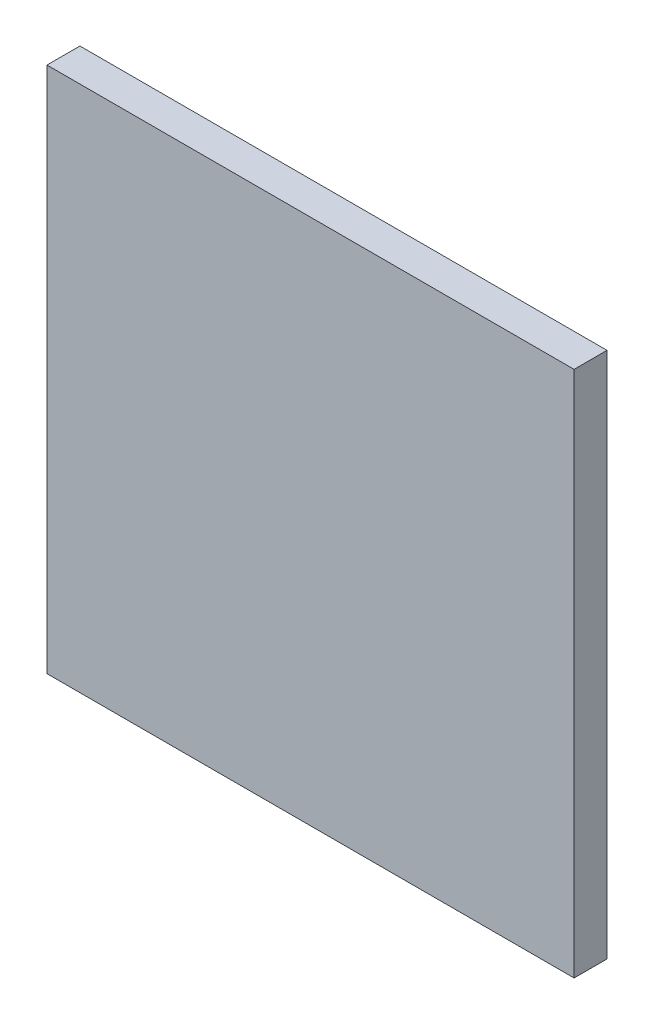
SolidWorks part; units mm, degrees
material "Pure Lead"
ref_plane "Front Plane" through (0, 0, 0) normal (0, 0, 1) x (1, 0, 0)
ref_plane "Top Plane" through (0, 0, 0) normal (0, 1, 0) x (1, 0, 0)
ref_plane "Right Plane" through (0, 0, 0) normal (1, 0, 0) x (0, 0, -1)
sketch "Sketch1" plane through (0, 0, 0) normal (0, 0, 1) x (1, 0, 0)
  line L1 (-9237.5412, -2277) -> (-8627.9412, -2277)
  line L2 (-9237.5412, -2277) -> (-9237.5412, -2886.6)
  line L3 (-9237.5412, -2886.6) -> (-8627.9412, -2886.6)
  line L4 (-8627.9412, -2277) -> (-8627.9412, -2886.6)
  line L5 (-9237.5412, -2277) -> (-8627.9412, -2886.6) construction
  line L6 (-9237.5412, -2886.6) -> (-8627.9412, -2277) construction
  point P0 (-8932.7412, -2581.8)
  dimension "D1" = 609.6
  dimension "D3" = 609.6
extrude "Boss-Extrude1" add sketch "Sketch1" along normal blind 38.1
